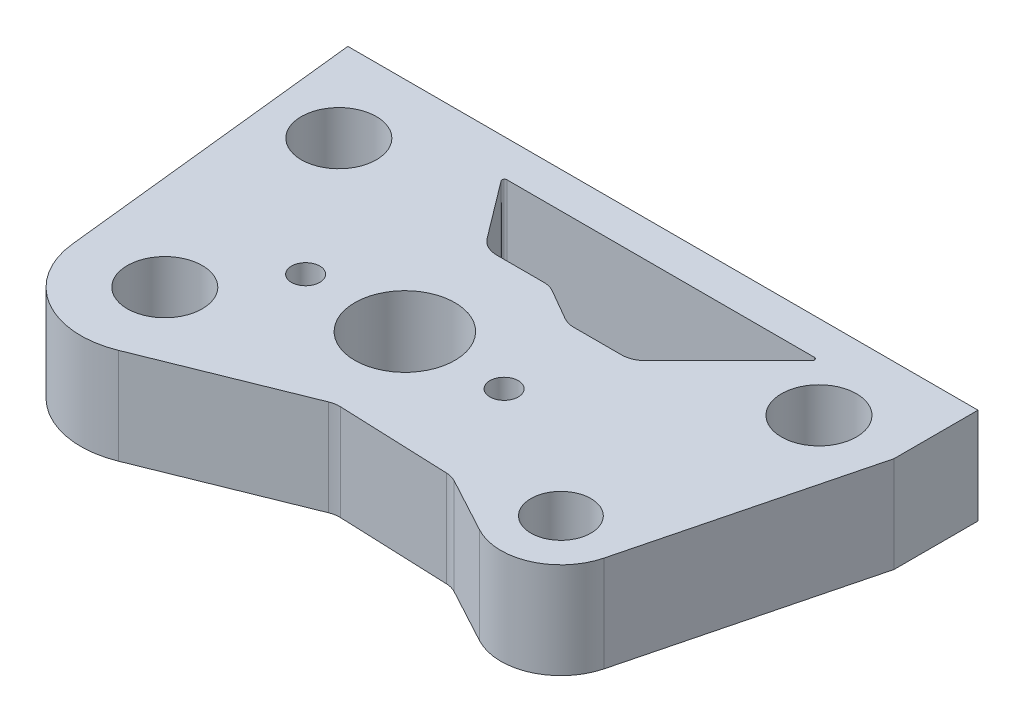
SolidWorks part; units mm, degrees
material "7075-T6 (SN)"
ref_plane "X-Y Datum" through (0, 0, 0) normal (0, 0, 1) x (1, 0, 0)
ref_plane "X-Z Datum" through (0, 0, 0) normal (0, 1, 0) x (1, 0, 0)
ref_plane "Y-Z Datum" through (0, 0, 0) normal (1, 0, 0) x (0, 0, -1)
sketch "Sketch1" plane through (0, 0, 0) normal (0, 1, 0) x (1, 0, 0)
  line L1 (54.2925, 13.97) -> (-12.3825, 13.97) construction
  line L4 (54.2925, 31.75) -> (-12.3825, 31.75)
  line L6 (46.355, 22.86) -> (-4.445, 22.86) construction
  line L7 (54.2925, 31.75) -> (54.2925, 13.97)
  line L8 (-12.3825, 31.75) -> (-12.3825, 13.97)
  line L21 (-7.9375, 0) -> (-12.3825, 13.97)
  line L22 (6.264, 8.509) -> (16.764, 8.509) construction
  line L24 (16.764, 8.509) -> (27.264, 8.509) construction
  line L25 (7.0861, -3.5764) -> (36.6629, -3.5764)
  line L27 (48.26, 0) -> (54.2925, 13.97)
  circle A0 centre (0, 0) radius 3.9688
  circle A1 centre (41.91, 0) radius 3.175
  circle A2 centre (46.355, 22.86) radius 3.9688
  circle A3 centre (-4.445, 22.86) radius 3.9687
  arc A5 (7.0861, -3.5764) -> (-7.9375, 0) centre (0, 0) cw
  circle A7 centre (16.764, 8.509) radius 5.3
  circle A8 centre (6.264, 8.509) radius 1.5
  circle A9 centre (27.264, 8.509) radius 1.5
  arc A10 (36.6629, -3.5764) -> (48.26, 0) centre (41.91, 0) ccw
  dimension "D2" = 6.35
  dimension "D7" = 7.9375
  dimension "D8" = 6.35
  dimension "D12" = 10.6
  dimension "D10" = 7.9375
  dimension "D17" = 3
  dimension "D19" = 7.9375
  dimension "D18" = 7.9375
  dimension "D3" = 50.8
  dimension "D4" = 17.78
  dimension "D5" = 8.89
  dimension "D6" = 31.75
  dimension "D9" = 4.445
  dimension "D11" = 7.9375
  dimension "D13" = 16.764
  dimension "D14" = 5.461
  dimension "D16" = 10.5
  dimension "D20" = 41.91
extrude "Boss-Extrude1" [suppressed] add sketch "Sketch1" against normal blind 10.16
sketch "Sketch3" [suppressed] plane through (0, 0, 0) normal (0, 1, 0) x (1, 0, 0)
  line L0 (0, 0) -> (0, -44.5462) construction
  line L1 (0, 0) -> (26.3151, -45.579) construction
  dimension "D1" = 30
other "Graphic1"
other "Graphic (Closed) -1"
other "Graphic2"
other "Graphic (Closed) -2"
sketch "Sketch4" plane through (0, 0, 0) normal (0, 1, 0) x (1, 0, 0)
  line L0 (54.2925, 22.86) -> (46.355, 22.86) construction
  line L1 (54.2925, 31.75) -> (-12.3825, 31.75)
  line L5 (27.264, 8.636) -> (16.764, 8.636) construction
  line L6 (16.764, 8.636) -> (6.264, 8.636) construction
  line L7 (46.355, 22.86) -> (-4.445, 22.86) construction
  line L8 (-4.445, 22.86) -> (-12.3825, 22.86) construction
  line L9 (54.2925, 13.97) -> (-12.3825, 13.97) construction
  line L10 (40.7888, 27.94) -> (8.2564, 27.94)
  line L11 (8.0536, 27.5331) -> (12.5949, 21.5067)
  line L12 (14.6234, 20.4953) -> (19.5738, 20.4953)
  line L13 (20.8438, 20.155) -> (24.0643, 18.2956)
  line L14 (25.3343, 17.9553) -> (30.3652, 17.9553)
  line L16 (32.1612, 18.6992) -> (40.9684, 27.5064)
  line L17 (-12.3825, 31.75) -> (-8.8383, -0.9577)
  line L19 (48.0631, -1.569) -> (54.2925, 22.86)
  line L20 (54.2925, 22.86) -> (54.2925, 31.75)
  line L21 (38.8939, -5.588) -> (33.0417, -2.4293)
  line L22 (31.9353, -2.1265) -> (20.241, -1.666)
  line L23 (19.1913, -1.8483) -> (3.324, -8.2452)
  circle A0 centre (0, 0) radius 3.9688
  circle A1 centre (46.355, 22.86) radius 3.9687
  circle A2 centre (-4.445, 22.86) radius 3.9688
  circle A3 centre (16.764, 8.636) radius 5.2959
  circle A4 centre (27.264, 8.636) radius 1.5
  circle A5 centre (6.264, 8.636) radius 1.5
  circle A6 centre (41.91, 0) radius 3.175
  arc A7 (12.5949, 21.5067) -> (14.6234, 20.4953) centre (14.6234, 23.0353) ccw
  arc A8 (19.5738, 20.4953) -> (20.8438, 20.155) centre (19.5738, 17.9553) cw
  arc A9 (24.0643, 18.2956) -> (25.3343, 17.9553) centre (25.3343, 20.4953) ccw
  arc A10 (30.3652, 17.9553) -> (32.1612, 18.6992) centre (30.3652, 20.4953) ccw
  arc A12 (8.2564, 27.94) -> (8.0536, 27.5331) centre (8.2564, 27.686) ccw
  arc A13 (40.7888, 27.94) -> (40.9684, 27.5064) centre (40.7888, 27.686) cw
  arc A14 (33.0417, -2.4293) -> (31.9353, -2.1265) centre (31.8353, -4.6645) ccw
  arc A15 (-8.8383, -0.9577) -> (3.324, -8.2452) centre (0, 0) ccw
  arc A16 (38.8939, -5.588) -> (48.0631, -1.569) centre (41.91, 0) ccw
  arc A17 (20.241, -1.666) -> (19.1913, -1.8483) centre (20.141, -4.204) ccw
  point P36 (13.357, 20.4953)
  point P39 (20.2543, 20.4953)
  point P42 (24.6538, 17.9553)
  point P51 (7.747, 27.94)
  point P54 (41.402, 27.94)
  point P59 (32.5236, -2.1497)
  point P62 (19.6966, -1.6446)
  dimension "D1" = 7.9375
  dimension "D2" = 7.9375
  dimension "D3" = 6.35
  dimension "D4" = 10.5918
  dimension "D5" = 3
  dimension "D27" = 2.54
  dimension "D28" = 0.254
  dimension "D29" = 6.35
  dimension "D30" = 8.89
  dimension "D35" = 2.54
  dimension "D6" = 10.5
  dimension "D7" = 22.86
  dimension "D8" = 50.8
  dimension "D9" = 7.9375
  dimension "D10" = 4.445
  dimension "D11" = 8.636
  dimension "D12" = 16.764
  dimension "D13" = 41.91
  dimension "D14" = 17.78
  dimension "D15" = 8.89
  dimension "D16" = 66.675
  dimension "D17" = 3.81
  dimension "D18" = 45
  dimension "D19" = 53
  dimension "D20" = 150
  dimension "D21" = 9.3218
  dimension "D22" = 33.655
  dimension "D23" = 12.192
  dimension "D24" = 24.5144
  dimension "D26" = 5.08
  dimension "D31" = 17.653
  dimension "D32" = 7.239
  dimension "D33" = 12.827
  dimension "D34" = 5.588
extrude "Boss-Extrude2" add sketch "Sketch4" along normal blind 10.16
ref_point "Point1"
ref_point "Point2"
sketch "Sketch5" plane through (0, 10.16, 0) normal (0, 1, 0) x (1, 0, 0)
  line L0 (0, 0) -> (0, -25.3617) construction
  line L1 (0, 0) -> (11.466, -19.8596) construction
  dimension "D1" = 30
